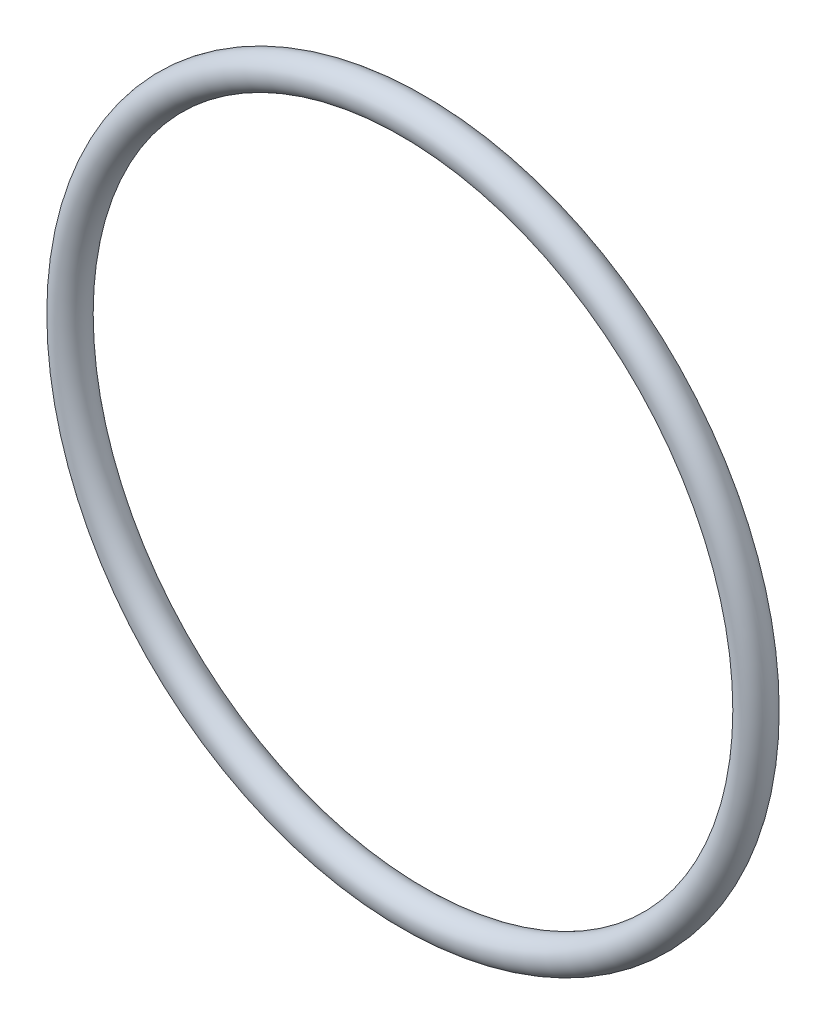
SolidWorks part; units mm, degrees
ref_plane "Front Plane" through (0, 0, 0) normal (0, 0, 1) x (1, 0, 0)
ref_plane "Top Plane" through (0, 0, 0) normal (0, 1, 0) x (1, 0, 0)
ref_plane "Right Plane" through (0, 0, 0) normal (1, 0, 0) x (0, 0, -1)
sketch "Sketch1" plane through (0, 0, 0) normal (0, 0, 1) x (1, 0, 0)
  line L0 (-28.6512, 0) -> (28.6512, 0) construction
  line L1 (-26.035, 0) -> (26.035, 0) construction
  line L2 (-20.2595, 20.2595) -> (20.2595, -20.2595) construction
  point P3 (26.035, 0)
  point P4 (0, 0)
  point P8 (0, 0)
  point P9 (0, 0)
  point P10 (-28.6512, 0)
  point P11 (-26.035, 0)
  point P14 (0, 0)
  point P15 (20.2595, -20.2595)
  point P16 (28.6512, 0)
  dimension "Actual OD" = 57.3024
  dimension "Actual ID" = 52.07
  dimension "Actual Width" = 2.6162
  dimension "D1" = 45
sketch "Sketch2" plane through (0, 0, 0) normal (0, 1, 0) x (1, 0, 0)
  line L0 (-28.6512, 0) -> (28.6512, 0) construction
  line L1 (-27.3431, 1.3081) -> (-27.3431, -1.3081) construction
  line L2 (0, -1.3081) -> (0, 1.3081) construction
  circle A0 centre (-27.3431, 0) radius 1.3081
  point P12 (0, 0)
revolve "Revolve1" add sketch "Sketch2" angle 360 about L2
sketch "Sketch3" plane through (0, 0, 0) normal (1, 0, 0) x (0, 0, -1)
  line L0 (-1.3081, 0) -> (1.3081, 0) construction
  line L1 (-1.3081, -19.5262) -> (-1.3081, 19.5262) construction
  point P4 (0, 0)
  point P7 (-1.3081, 0)
  point P9 (-1.3081, -19.5262)
  dimension "D1" = 2.6162
  dimension "D2" = 39.0525
equation "\"D1@Sketch3\"=\"Actual Width@Sketch1\""
equation "\"D2@Sketch3\"=\"Actual ID@Sketch1\"*.75"
